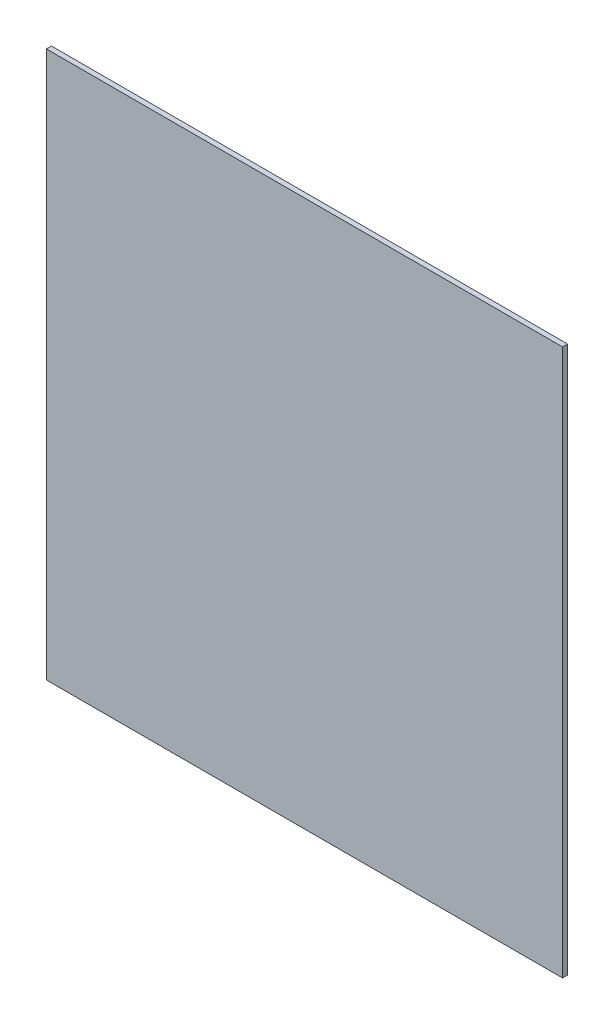
SolidWorks part; units mm, degrees
ref_plane "Front" through (0, 0, 0) normal (0, 0, 1) x (1, 0, 0)
ref_plane "Top" through (0, 0, 0) normal (0, 1, 0) x (1, 0, 0)
ref_plane "Right" through (0, 0, 0) normal (1, 0, 0) x (0, 0, -1)
sketch "Эскиз1" plane through (0, 0, 0) normal (0, 0, 1) x (1, 0, 0)
  line L1 (606, 648) -> (-6, 648)
  line L2 (606, 648) -> (606, 0)
  line L3 (606, 0) -> (-6, 0)
  line L4 (-6, 648) -> (-6, 0)
  dimension "D1" = 612
  dimension "D2" = 648
extrude "Бобышка-Вытянуть1" add sketch "Эскиз1" along normal blind 6
